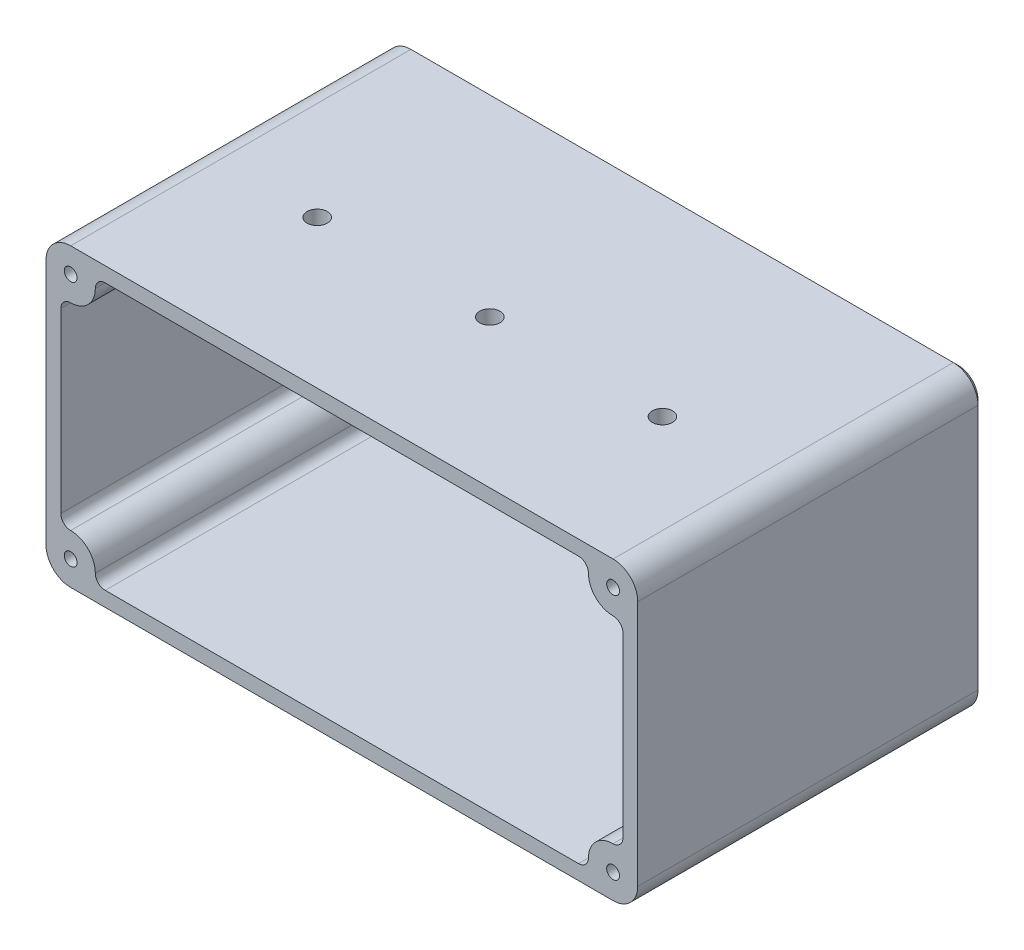
SolidWorks part; units mm, degrees
ref_plane "Front Plane" through (0, 0, 0) normal (0, 0, 1) x (1, 0, 0)
ref_plane "Top Plane" through (0, 0, 0) normal (0, 1, 0) x (1, 0, 0)
ref_plane "Right Plane" through (0, 0, 0) normal (1, 0, 0) x (0, 0, -1)
sketch "Sketch1" plane through (0, 0, 0) normal (0, 0, 1) x (1, 0, 0)
  line L1 (-60, 30) -> (60, 30)
  line L2 (-60, 30) -> (-60, -30)
  line L3 (-60, -30) -> (60, -30)
  line L4 (60, 30) -> (60, -30)
  line L5 (-60, 30) -> (60, -30) construction
  line L6 (-60, -30) -> (60, 30) construction
  point P0 (0, 0)
  dimension "D1" = 120
  dimension "D2" = 60
extrude "Boss-Extrude1" add sketch "Sketch1" along normal blind 70
sketch "Sketch2" plane through (0, 0, 70) normal (0, 0, 1) x (1, 0, 0)
  line L0 (60, 30) -> (-60, 30) construction
  line L1 (-57, 27) -> (57, 27)
  line L2 (-57, 27) -> (-57, -27)
  line L3 (-57, -27) -> (57, -27)
  line L4 (57, 27) -> (57, -27)
  line L5 (-57, 27) -> (57, -27) construction
  line L6 (-57, -27) -> (57, 27) construction
  line L7 (60, -30) -> (60, 30) construction
  point P0 (0, 0)
  dimension "D1" = 3
  dimension "D2" = 3
extrude "Cut-Extrude1" cut sketch "Sketch2" against normal offset from surface (67 mm away) 3 up to face at (0, 0, 0)
fillet "Fillet3" radius 5 4 edges at (-60, -30, 35) (60, -30, 35) (60, 30, 35) (-60, 30, 35)
fillet "Fillet4" radius 2 4 edges at (57, 27, 36.5) (57, -27, 36.5) (-57, -27, 36.5) (-57, 27, 36.5)
sketch "Sketch4" plane through (0, 0, 70) normal (0, 0, 1) x (1, 0, 0)
  line L0 (55, 30) -> (-55, 30) construction
  line L1 (0, -33) -> (0, 33) construction
  line L2 (44, 0) -> (-44, 0) construction
  circle A0 centre (-55, 25) radius 5
  circle A1 centre (55, 25) radius 5
  circle A2 centre (55, -25) radius 5
  circle A3 centre (-55, -25) radius 5
extrude "Boss-Extrude3" add sketch "Sketch4" against normal up to surface (67 mm away) up to face at (0, 0, 3)
fillet "Fillet5" radius 2 8 edges at (-57, -20.4174, 36.5) (-50.4174, -27, 36.5) (50.4174, -27, 36.5) (57, -20.4174, 36.5) (57, 20.4174, 36.5) (50.4174, 27, 36.5) (-57, 20.4174, 36.5) (-50.4174, 27, 36.5)
sketch "Sketch5" plane through (0, 0, 70) normal (0, 0, 1) x (1, 0, 0)
  circle A0 centre (-55, 25) radius 1.3
  circle A1 centre (55, 25) radius 1.3
  circle A2 centre (55, -25) radius 1.3
  circle A3 centre (-55, -25) radius 1.3
  dimension "D1" = 2.6
extrude "Cut-Extrude2" cut sketch "Sketch5" against normal blind 18
sketch "Sketch6" plane through (0, 30, 0) normal (0, 1, 0) x (1, 0, 0)
  circle A0 centre (0, -40) radius 2.05
  circle A1 centre (35, -40) radius 2.05
  circle A2 centre (-35, -40) radius 2.05
  point P6 (0, 0)
  point P8 (0, 0)
  dimension "D4" = 4.1
  dimension "D1" = 40
  dimension "D2" = 70
  dimension "D3" = 35
extrude "Cut-Extrude3" cut sketch "Sketch6" against normal blind 3
chamfer "Chamfer2" distance 1 angle 45 8 edges at (0, 30, 0) (-58.5355, 28.5355, 0) (58.5355, 28.5355, 0) (-60, 0, 0) (60, 0, 0) (-58.5355, -28.5355, 0) (58.5355, -28.5355, 0) (0, -30, 0)
sketch "Sketch7" plane through (0, 0, 0) normal (0, 0, -1) x (-1, 0, 0)
  circle A0 centre (-43, -18) radius 6.25
  dimension "D1" = 12.5
  dimension "D2" = 43
  dimension "D3" = 18
extrude "Cut-Extrude4" cut sketch "Sketch7" against normal through all
sketch "Sketch8" plane through (0, 0, 3) normal (0, 0, 1) x (1, 0, 0)
  circle A0 centre (43, -18) radius 8.75
  dimension "D1" = 17.5
extrude "Cut-Extrude5" cut sketch "Sketch8" against normal blind 1.5
